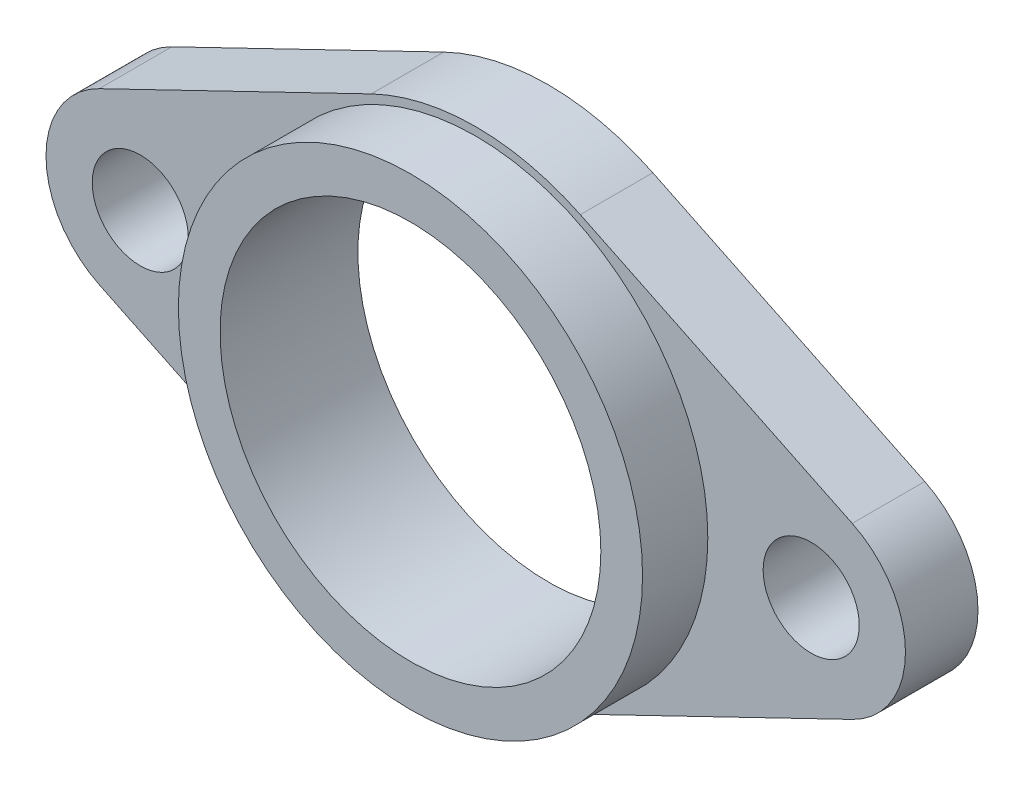
SolidWorks part; units mm, degrees
ref_plane "Front Plane" through (0, 0, 0) normal (0, 0, 1) x (1, 0, 0)
ref_plane "Top Plane" through (0, 0, 0) normal (0, 1, 0) x (1, 0, 0)
ref_plane "Right Plane" through (0, 0, 0) normal (1, 0, 0) x (0, 0, -1)
sketch "Layout Sketch" plane through (0, 0, 0) normal (0, 0, 1) x (1, 0, 0)
  line L0 (0, 0) -> (0, 14.778) construction
  circle A0 centre (-18.5, 0) radius 1 construction
  circle A1 centre (18.5, 0) radius 1 construction
  dimension "D1" = 2
  dimension "D2" = 37
sketch "Base Sketch" plane through (0, 0, 0) normal (0, 0, 1) x (1, 0, 0)
  line L0 (-20.7627, 4.6819) -> (-5.7655, 11.9298)
  line L1 (-20.7627, -4.6819) -> (-5.7655, -11.9298)
  line L2 (5.7655, 11.9298) -> (20.7627, 4.6819)
  line L3 (20.7627, -4.6819) -> (5.7655, -11.9298)
  line L4 (0, 0) -> (7.7453, 0) construction
  arc A0 (-20.7627, 4.6819) -> (-20.7627, -4.6819) centre (-18.5, 0) ccw
  arc A1 (20.7627, -4.6819) -> (20.7627, 4.6819) centre (18.5, 0) ccw
  arc A2 (-5.7655, -11.9298) -> (5.7655, -11.9298) centre (0, 0) ccw
  arc A3 (5.7655, 11.9298) -> (-5.7655, 11.9298) centre (0, 0) ccw
  circle A4 centre (0, 0) radius 10.5
  dimension "D1" = 26.5
  dimension "D2" = 5.2
  dimension "D3" = 21
extrude "Base Extrude" add sketch "Base Sketch" along normal blind 4
sketch "Bearing Retaining Ring Sketch" plane through (0, 0, 0) normal (0, 0, 1) x (1, 0, 0)
  circle A0 centre (0, 0) radius 10.5
  circle A1 centre (0, 0) radius 12.8
  circle A3 centre (0, 0) radius 10.5 construction
  point P4 (0, 0)
  dimension "D1" = 25.6
extrude "Bearing Retaining Ring" add sketch "Bearing Retaining Ring Sketch" along normal blind 7.6
hole_wizard "Mounting Holes" positions "Mounting Holes Position Sketch" profile "Mounting Holes Profile Sketch" hole size "M5" standard "ANSI Metric" end condition up to next
sketch "Mounting Holes Position Sketch" plane through (0, 0, 0) normal (0, 0, -1) x (-1, 0, 0)
  point P0 (18.5, 0)
  point P3 (-18.5, 0)
sketch "Mounting Holes Profile Sketch" plane through (-18.5, 0, 0) normal (1, 0, 0) x (0, 1, 0)
  line L0 (0, 0) -> (0, 4)
  line L1 (0, 4) -> (2.65, 4)
  line L2 (2.65, 4) -> (2.65, 0)
  line L5 (2.65, 0) -> (0, 0)
  line L11 (0, -6.35) -> (0, 107.95) construction
  dimension "Thru Hole Dia." = 5.3
  dimension "Thru Hole Depth" = 4
